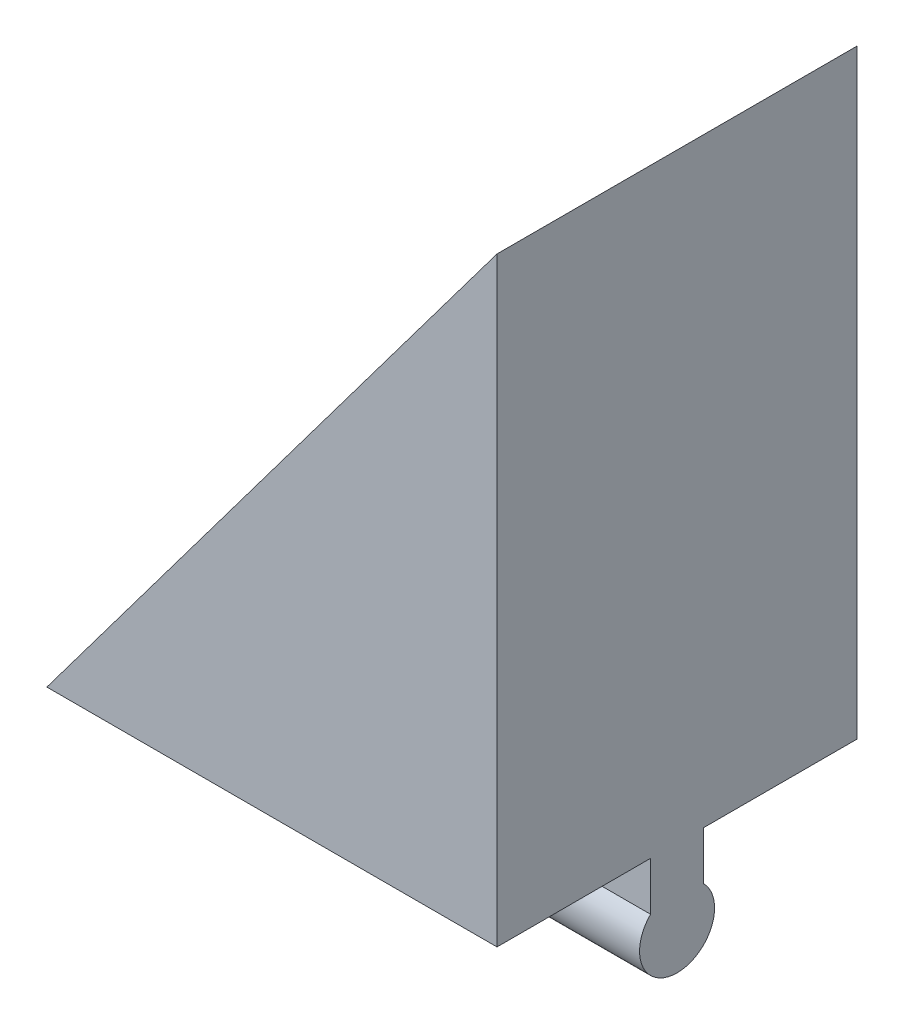
SolidWorks part; units mm, degrees
ref_plane "前视基准面" through (0, 0, 0) normal (0, 0, 1) x (1, 0, 0)
ref_plane "上视基准面" through (0, 0, 0) normal (0, 1, 0) x (1, 0, 0)
ref_plane "右视基准面" through (0, 0, 0) normal (1, 0, 0) x (0, 0, -1)
sketch "草图1" plane through (0, 0, 0) normal (0, 0, 1) x (1, 0, 0)
  line L0 (0, 0) -> (50000, 0) construction
  line L1 (0, 0) -> (0, 50000) construction
  line L2 (-15, -17) -> (15, -17)
  line L3 (-15, 23) -> (15, 23)
  line L4 (-15, 23) -> (-15, -23)
  line L5 (-15, -23) -> (15, -23)
  line L6 (15, 23) -> (15, -23)
  line L7 (15, 23) -> (-15, -17)
  dimension "D1" = 30
  dimension "D2" = 46
  dimension "D3" = 6
extrude "凸台-拉伸1" add sketch "草图1" along normal blind 24 contours L6 L7 L2 | L6 L2 L4 L5
sketch "草图2" plane through (-15, 0, 0) normal (-1, 0, 0) x (0, 0, 1)
  line L0 (12, -23) -> (12, 49977) construction
  line L1 (24, -23) -> (0, -23) construction
  line L2 (0, -20) -> (50000, -20) construction
  line L3 (0, -17) -> (0, -23) construction
  line L4 (24, -17) -> (0, -17) construction
  line L5 (4, -17) -> (20, -17)
  line L6 (4, -17) -> (4, -23)
  line L7 (4, -23) -> (20, -23)
  line L8 (20, -17) -> (20, -23)
  line L9 (24, -17) -> (24, -23) construction
  point P4 (12, -23)
  point P9 (0, -20)
  dimension "D1" = 4
extrude "切除-拉伸1" cut sketch "草图2" against normal through all contours L6 L5 L8 L7
sketch "草图3" plane through (-15, 0, 0) normal (-1, 0, 0) x (0, 0, 1)
  line L1 (0, -23) -> (4, -23)
  line L2 (0, -23) -> (0, -27)
  line L3 (0, -27) -> (4, -27)
  line L4 (4, -23) -> (4, -27)
  line L5 (20, -23) -> (24, -23)
  line L6 (20, -23) -> (20, -27)
  line L7 (20, -27) -> (24, -27)
  line L8 (24, -23) -> (24, -27)
extrude "凸台-拉伸2" add sketch "草图3" against normal blind 30
sketch "草图4" plane through (0, -17, 0) normal (0, -1, 0) x (1, 0, 0)
  line L0 (-15, 12) -> (49985, 12) construction
  line L1 (-15, 4) -> (-15, 20) construction
  line L2 (0, 0) -> (0, 50000) construction
  line L3 (15, 4) -> (15, 20) construction
  line L4 (-15, 14) -> (11, 14)
  line L5 (-15, 14) -> (-15, 10)
  line L6 (-15, 10) -> (11, 10)
  line L7 (11, 14) -> (11, 10)
  point P4 (-15, 12)
  dimension "D1" = 4
  dimension "D2" = 4
extrude "凸台-拉伸3" add sketch "草图4" along normal blind 10
sketch "草图5" plane through (15, 0, 0) normal (1, 0, 0) x (0, 0, -1)
  line L1 (-4, -17) -> (0, -17)
  line L2 (-4, -17) -> (-4, -27)
  line L3 (-4, -27) -> (0, -27)
  line L4 (0, -17) -> (0, -27)
  line L5 (-20, -17) -> (-24, -17)
  line L6 (-20, -17) -> (-20, -27)
  line L7 (-20, -27) -> (-24, -27)
  line L8 (-24, -17) -> (-24, -27)
extrude "切除-拉伸3" cut sketch "草图5" against normal through all
sketch "草图6" plane through (-15, 0, 0) normal (-1, 0, 0) x (0, 0, 1)
  line L1 (10, -17) -> (14, -17)
  line L2 (10, -17) -> (10, -27)
  line L3 (10, -27) -> (14, -27)
  line L4 (14, -17) -> (14, -27)
extrude "切除-拉伸5" cut sketch "草图6" against normal through all
sketch "草图7" plane through (15, 0, 0) normal (1, 0, 0) x (0, 0, -1)
  line L0 (-12, -17) -> (-12, 49983) construction
  line L1 (0, -17) -> (-24, -17) construction
  circle A0 centre (-12, -21) radius 4
  point P4 (-12, -17)
  point P7 (-12, -20.8453)
  point P8 (0, 0)
extrude "凸台-拉伸5" add sketch "草图7" against normal blind 30 separate body
sketch "草图8" plane through (15, 0, 0) normal (1, 0, 0) x (0, 0, -1)
  circle A0 centre (-12, -21) radius 4
extrude "切除-拉伸6" cut sketch "草图8" against normal blind 4
sketch "草图9" plane through (11, 0, 0) normal (1, 0, 0) x (0, 0, -1)
  circle A0 centre (-12, -21) radius 4
extrude "切除-拉伸7" cut sketch "草图9" against normal through all
sketch "草图10" plane through (15, 0, 0) normal (1, 0, 0) x (0, 0, -1)
  line L0 (-12, -17) -> (-12, 49983) construction
  line L1 (0, -17) -> (-24, -17) construction
  line L2 (-12, -17) -> (49988, -17) construction
  line L4 (-13.615, -17) -> (-10.385, -17)
  line L5 (-13.615, -17) -> (-13.615, -20.54)
  line L6 (-13.615, -20.54) -> (-10.385, -20.54)
  line L7 (-10.385, -17) -> (-10.385, -20.54)
  point P4 (-12, -17)
extrude "凸台-拉伸6" add sketch "草图10" against normal blind 30
sketch "草图11" plane through (15, 0, 0) normal (1, 0, 0) x (0, 0, -1)
  line L0 (-12, -20.54) -> (-12, 49979.46) construction
  line L1 (-13.615, -20.54) -> (-10.385, -20.54) construction
  line L3 (-13.615, -17) -> (-10.385, -17)
  line L4 (-13.615, -17) -> (-13.615, -20.54)
  line L5 (-13.615, -20.54) -> (-10.385, -20.54)
  line L6 (-10.385, -17) -> (-10.385, -20.54)
  point P4 (-12, -20.54)
extrude "切除-拉伸8" cut sketch "草图11" against normal through all
sketch "草图12" plane through (15, 0, 0) normal (1, 0, 0) x (0, 0, -1)
  line L0 (-12, -17) -> (-12, 49983) construction
  line L1 (0, -17) -> (-24, -17) construction
  line L2 (-12, -21.9978) -> (-10.2322, -20.23)
  line L3 (-13.7678, -17) -> (-10.2322, -17)
  line L4 (-13.7678, -17) -> (-13.7678, -20.23)
  line L5 (-13.7678, -20.23) -> (-10.2322, -20.23)
  line L6 (-10.2322, -17) -> (-10.2322, -20.23)
  line L7 (-12, -21.9978) -> (-13.7678, -20.23)
  circle A0 centre (-12, -21.9978) radius 2.5
  point P4 (-12, -17)
  point P11 (0, 0)
  point P14 (0, 0)
  point P15 (-12, -24.3479)
  point P16 (-12, -24.1009)
  point P17 (-12, -22.6461)
  point P18 (0, 0)
  point P19 (0, 0)
  line M10 (-24, -17) -> (0, -17)
  dimension "D1" = 5
  dimension "D2" = 90
  dimension "D3" = 45
  dimension "D4" = 3.23
extrude "凸台-拉伸7" add sketch "草图12" against normal blind 30 contours A0 L0 L4 M10 | L0 A0 L6 L3 | L7 L0 L5 | L5 L0 A0 | L0 L5 A0 | L0 L2 L5 | L0 A0 L2 | A0 L0 L7
